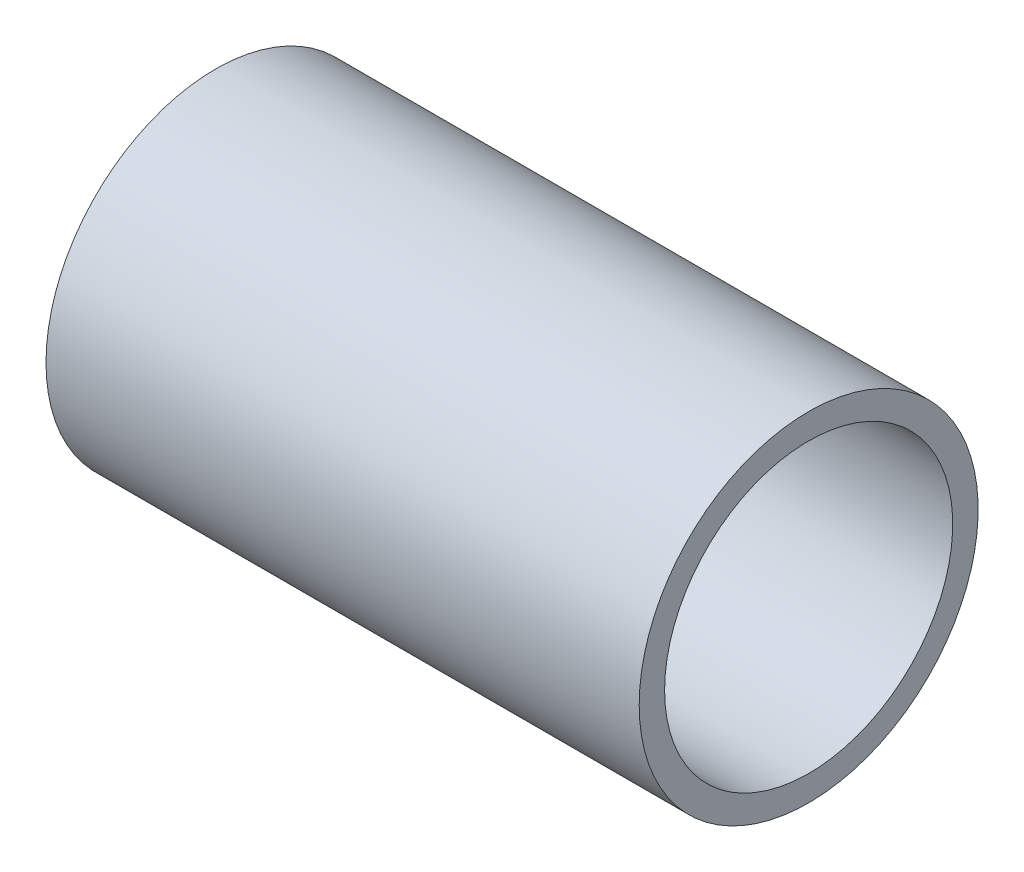
SolidWorks part; units mm, degrees
material "Galvanized Steel"
ref_plane "Front Plane" through (0, 0, 0) normal (0, 0, 1) x (1, 0, 0)
ref_plane "Top Plane" through (0, 0, 0) normal (0, 1, 0) x (1, 0, 0)
ref_plane "Right Plane" through (0, 0, 0) normal (1, 0, 0) x (0, 0, -1)
sketch "Sketch1" plane through (0, 0, 0) normal (0, 0, 1) x (1, 0, 0)
  line L1 (-117.1152, 0) -> (96.2241, 0) construction
  line L2 (338.2958, 20) -> (338.2958, 17)
  line L10 (268.2958, 20) -> (338.2958, 20)
  line L11 (338.2958, 17) -> (313.2958, 17)
  line L12 (313.2958, 17) -> (313.2958, 14.5)
  line L13 (313.2958, 14.5) -> (268.5447, 14.5)
  arc A0 (268.2958, 20) -> (268.5447, 14.5) centre (-107.6846, 0.2261) cw
  dimension "D1" = 3
  dimension "D3" = 2.5
  dimension "D9" = 376.5
  dimension "D2" = 17
  dimension "D4" = 14.5
  dimension "D5" = 44.751
  dimension "D6" = 25
  dimension "D7" = 70
revolve "Revolve2" add sketch "Sketch1" angle 360 about L1
